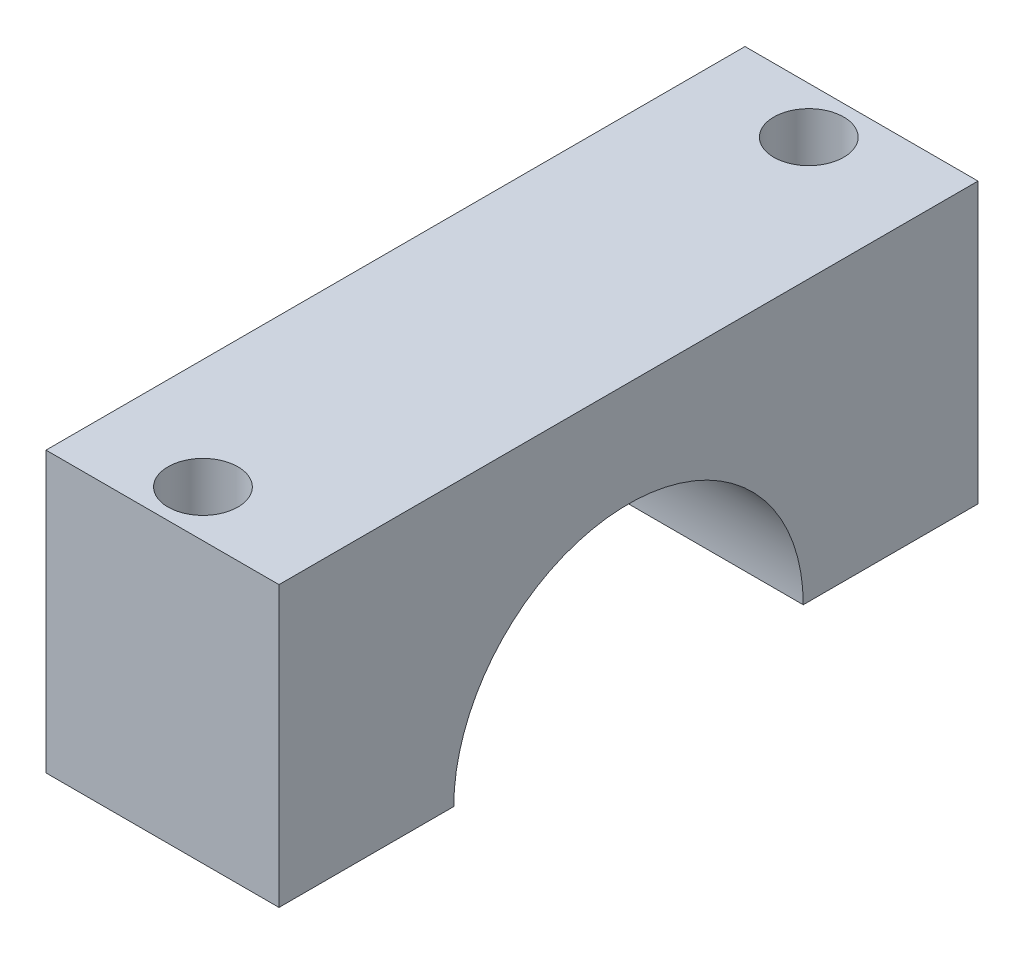
SolidWorks part; units mm, degrees
ref_plane "Front Plane" through (0, 0, 0) normal (0, 0, 1) x (1, 0, 0)
ref_plane "Top Plane" through (0, 0, 0) normal (0, 1, 0) x (1, 0, 0)
ref_plane "Right Plane" through (0, 0, 0) normal (1, 0, 0) x (0, 0, -1)
sketch "Sketch1" plane through (0, 0, 0) normal (1, 0, 0) x (0, 0, -1)
  line L0 (0, -54.9042) -> (0, 63.4026) construction
  line L1 (0, 0) -> (-30, 0)
  line L2 (-30, 0) -> (-30, 24)
  line L3 (-30, 24) -> (30, 24)
  line L4 (30, 24) -> (30, 0)
  line L5 (30, 0) -> (0, 0)
  dimension "D1" = 30
  dimension "D2" = 30
  dimension "D3" = 24
extrude "Boss-Extrude1" add sketch "Sketch1" against normal blind 20
sketch "Sketch6" plane through (0, 24, 0) normal (0, 1, 0) x (1, 0, 0)
  line L0 (-20, 30) -> (0, 30) construction
  line L1 (-20, -30) -> (0, -30) construction
  circle A1 centre (-10.5271, 26) radius 3
  circle A2 centre (-10.5271, -26) radius 3
  dimension "D1" = 4
  dimension "D2" = 4
sketch "Sketch7" plane through (-20, 0, 0) normal (-1, 0, 0) x (0, 0, 1)
  circle A0 centre (0, 0) radius 15
  dimension "D1" = 30
sketch "Sketch9" plane through (-20, 0, 0) normal (-1, 0, 0) x (0, 0, 1)
  line L0 (-15, 0) -> (-15, 24)
  line L1 (30, 0) -> (-30, 0) construction
  line L2 (-23, 24) -> (-29, 24) construction
  circle A0 centre (0, 0) radius 15 construction
sketch "Sketch10" plane through (0, 24, 0) normal (0, 1, 0) x (1, 0, 0)
  line L0 (-20, 17.5) -> (0, 17.5)
  line L1 (-20, 15) -> (-20, -15) construction
  line L2 (0, 30) -> (0, -30) construction
extrude "Cut-Extrude1" cut sketch "Sketch7" against normal blind 20 contours A0
extrude "Cut-Extrude2" cut sketch "Sketch6" against normal blind 24
